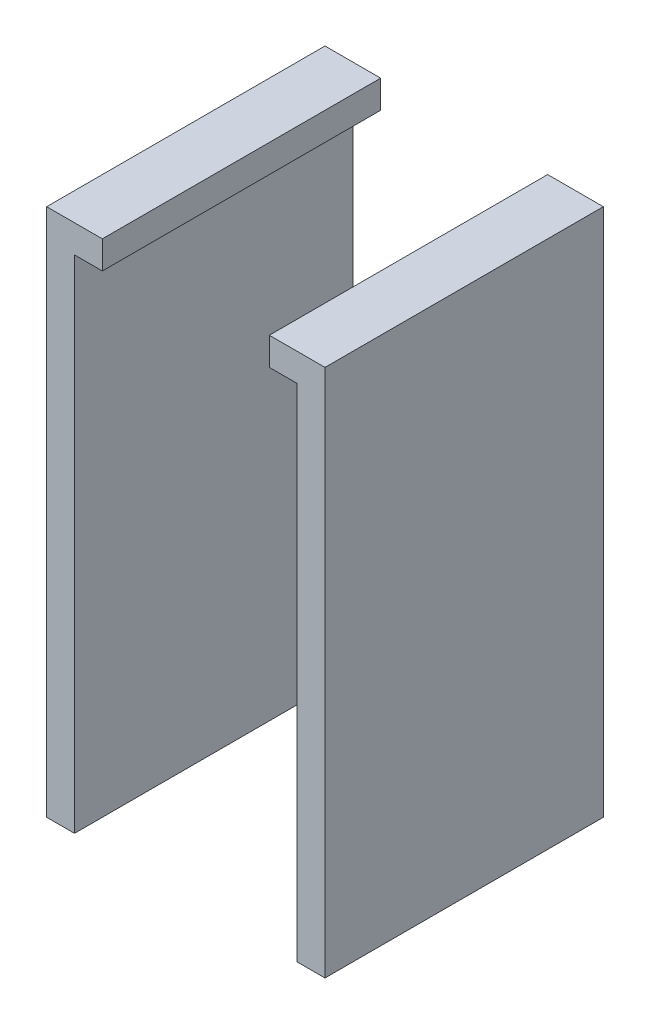
SolidWorks part; units mm, degrees
ref_plane "Front Plane" through (0, 0, 0) normal (0, 0, 1) x (1, 0, 0)
ref_plane "Top Plane" through (0, 0, 0) normal (0, 1, 0) x (1, 0, 0)
ref_plane "Right Plane" through (0, 0, 0) normal (1, 0, 0) x (0, 0, -1)
sketch "Sketch1" plane through (0, 0, 0) normal (0, 0, 1) x (1, 0, 0)
  line L0 (0, 0) -> (0, 285)
  line L1 (0, 285) -> (30, 285)
  line L2 (30, 285) -> (30, 270)
  line L3 (30, 270) -> (15, 270)
  line L4 (15, 270) -> (15, 0)
  line L5 (15, 0) -> (0, 0)
  line L6 (135, 0) -> (135, 270)
  line L7 (135, 270) -> (120, 270)
  line L8 (120, 270) -> (120, 285)
  line L9 (120, 285) -> (150, 285)
  line L10 (150, 285) -> (150, 0)
  line L11 (150, 0) -> (135, 0)
  point P9 (30, 277.5)
  dimension "D1" = 285
  dimension "D2" = 15
  dimension "D3" = 15
  dimension "D4" = 30
  dimension "D6" = 90
extrude "Boss-Extrude1" add sketch "Sketch1" along normal blind 150
